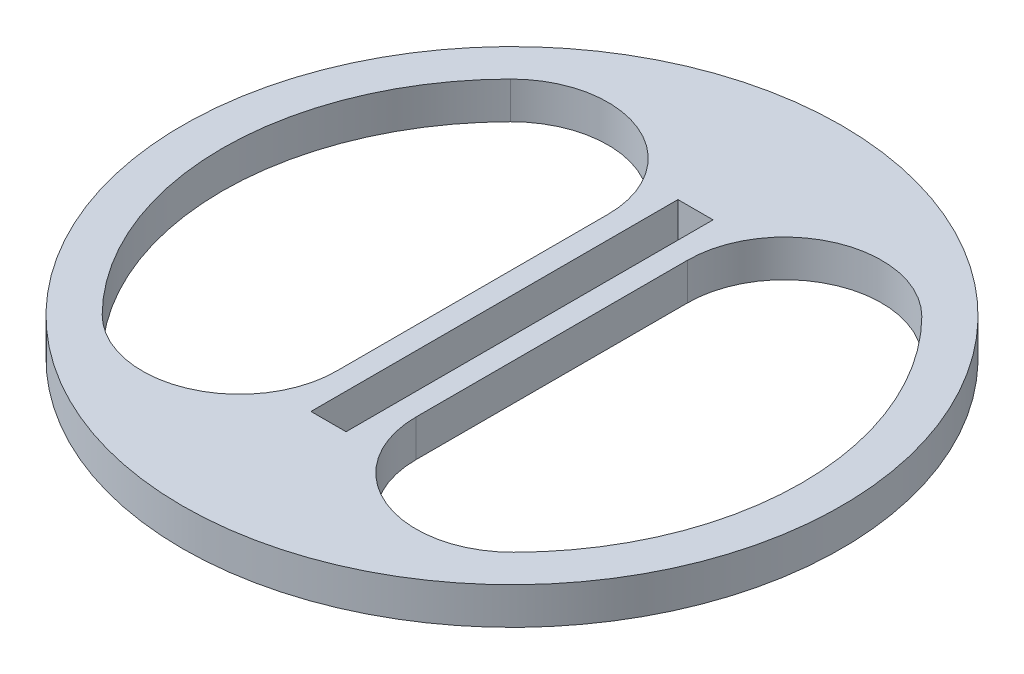
SolidWorks part; units mm, degrees
ref_plane "Front Plane" through (0, 0, 0) normal (0, 0, 1) x (1, 0, 0)
ref_plane "Top Plane" through (0, 0, 0) normal (0, 1, 0) x (1, 0, 0)
ref_plane "Right Plane" through (0, 0, 0) normal (1, 0, 0) x (0, 0, -1)
sketch "Sketch1" plane through (0, 0, 0) normal (0, 1, 0) x (1, 0, 0)
  line L0 (4.3, 0) -> (-4.3, 0)
  line L1 (4.3, -31.0537) -> (4.3, 31.0537)
  line L2 (-4.3, -31.0537) -> (-4.3, 31.0537)
  line L4 (1.9, -19.85) -> (-1.9, -19.85)
  line L5 (1.9, -19.85) -> (1.9, 19.85)
  line L6 (1.9, 19.85) -> (-1.9, 19.85)
  line L7 (-1.9, -19.85) -> (-1.9, 19.85)
  line L8 (1.9, -19.85) -> (-1.9, 19.85) construction
  line L9 (1.9, 19.85) -> (-1.9, -19.85) construction
  circle A0 centre (0, 0) radius 35.65
  arc A1 (-4.3, 31.0537) -> (-4.3, -31.0537) centre (0, 0) ccw
  circle A2 centre (0, 0) radius 31.35 construction
  arc A3 (4.3, -31.0537) -> (4.3, 31.0537) centre (0, 0) ccw
  point P16 (0, 0)
  dimension "D1" = 71.3
  dimension "D3" = 8.6
  dimension "D4" = 8.6
  dimension "D5" = 3.8
  dimension "D6" = 39.7
  dimension "D2" = 4.3
extrude "Boss-Extrude1" add sketch "Sketch1" along normal blind 4
fillet "Fillet1" radius 10.5 4 edges at (-4.3, 2, -31.0537) (-4.3, 2, 31.0537) (4.3, 2, 31.0537) (4.3, 2, -31.0537)
